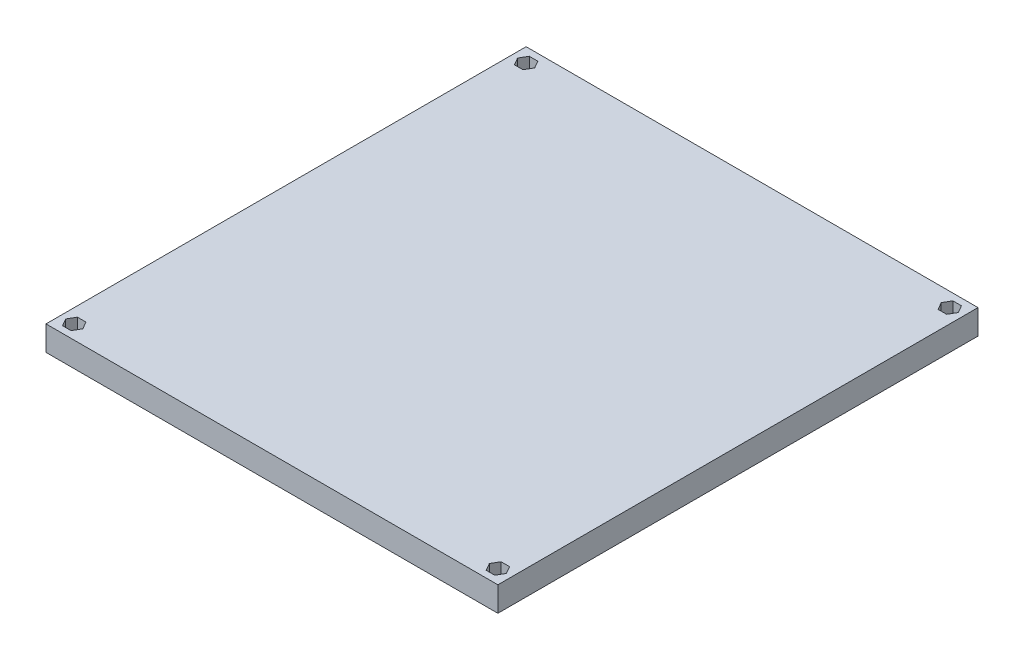
SolidWorks part; units mm, degrees
ref_plane "Front Plane" through (0, 0, 0) normal (0, 0, 1) x (1, 0, 0)
ref_plane "Top Plane" through (0, 0, 0) normal (0, 1, 0) x (1, 0, 0)
ref_plane "Right Plane" through (0, 0, 0) normal (1, 0, 0) x (0, 0, -1)
sketch "Sketch1" plane through (0, 0, 0) normal (0, 1, 0) x (1, 0, 0)
  line L1 (0, 0) -> (64, 0)
  line L2 (0, 0) -> (0, -68)
  line L3 (0, -68) -> (64, -68)
  line L4 (64, 0) -> (64, -68)
  dimension "D1" = 64
  dimension "D2" = 68
extrude "Boss-Extrude1" add sketch "Sketch1" along normal blind 3.5
sketch "Sketch2" plane through (0, 3.5, 0) normal (0, 1, 0) x (1, 0, 0)
  line L0 (64, -68) -> (64, 0) construction
  line L1 (2, -2) -> (62, -2) construction
  line L2 (2, -2) -> (2, -66) construction
  line L3 (2, -66) -> (62, -66) construction
  line L4 (62, -2) -> (62, -66) construction
  line L5 (0, -68) -> (64, -68) construction
  line L6 (0, 0) -> (0, -68) construction
  line L7 (64, 0) -> (0, 0) construction
  line L9 (3.2124, -2) -> (2.6062, -0.95)
  line L10 (2.6062, -0.95) -> (1.3938, -0.95)
  line L11 (1.3938, -0.95) -> (0.7876, -2)
  line L12 (0.7876, -2) -> (1.3938, -3.05)
  line L13 (1.3938, -3.05) -> (2.6062, -3.05)
  line L14 (2.6062, -3.05) -> (3.2124, -2)
  line L15 (60.7876, -2) -> (61.3938, -3.05)
  line L16 (61.3938, -3.05) -> (62.6062, -3.05)
  line L17 (62.6062, -3.05) -> (63.2124, -2)
  line L18 (63.2124, -2) -> (62.6062, -0.95)
  line L19 (62.6062, -0.95) -> (61.3938, -0.95)
  line L20 (61.3938, -0.95) -> (60.7876, -2)
  line L21 (60.7876, -66) -> (61.3938, -67.05)
  line L22 (61.3938, -67.05) -> (62.6062, -67.05)
  line L23 (62.6062, -67.05) -> (63.2124, -66)
  line L24 (63.2124, -66) -> (62.6062, -64.95)
  line L25 (62.6062, -64.95) -> (61.3938, -64.95)
  line L26 (61.3938, -64.95) -> (60.7876, -66)
  line L27 (3.2124, -66) -> (2.6062, -64.95)
  line L28 (2.6062, -64.95) -> (1.3938, -64.95)
  line L29 (1.3938, -64.95) -> (0.7876, -66)
  line L30 (0.7876, -66) -> (1.3938, -67.05)
  line L31 (1.3938, -67.05) -> (2.6062, -67.05)
  line L32 (2.6062, -67.05) -> (3.2124, -66)
  circle A0 centre (2, -2) radius 1.05 construction
  circle A1 centre (62, -2) radius 1.05 construction
  circle A2 centre (62, -66) radius 1.05 construction
  circle A3 centre (2, -66) radius 1.05 construction
  dimension "D5" = 2.1
  dimension "D1" = 2
  dimension "D2" = 2
  dimension "D3" = 2
  dimension "D4" = 2
extrude "Cut-Extrude1" cut sketch "Sketch2" against normal blind 2.3
